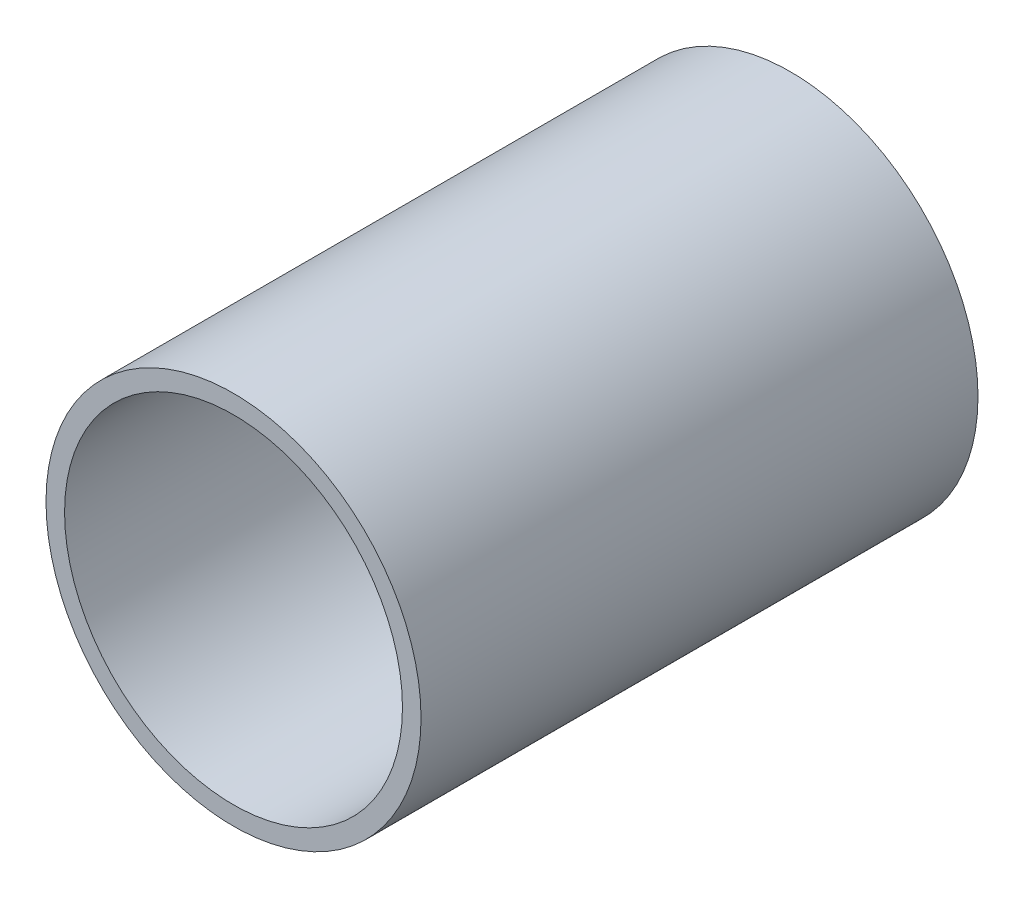
SolidWorks part; units mm, degrees
material "Латунь"
ref_plane "Спереди" through (0, 0, 0) normal (0, 0, 1) x (1, 0, 0)
ref_plane "Сверху" through (0, 0, 0) normal (0, 1, 0) x (1, 0, 0)
ref_plane "Справа" through (0, 0, 0) normal (1, 0, 0) x (0, 0, -1)
other "Configuration Table"
sketch "Эскиз1" plane through (0, 0, 0) normal (0, 0, 1) x (1, 0, 0)
  circle A0 centre (0, 0) radius 10.1
  circle A1 centre (0, 0) radius 9.1
  dimension "D1" = 20.2
  dimension "D2" = 1
extrude "Бобышка-Вытянуть1" add sketch "Эскиз1" along normal blind 30
